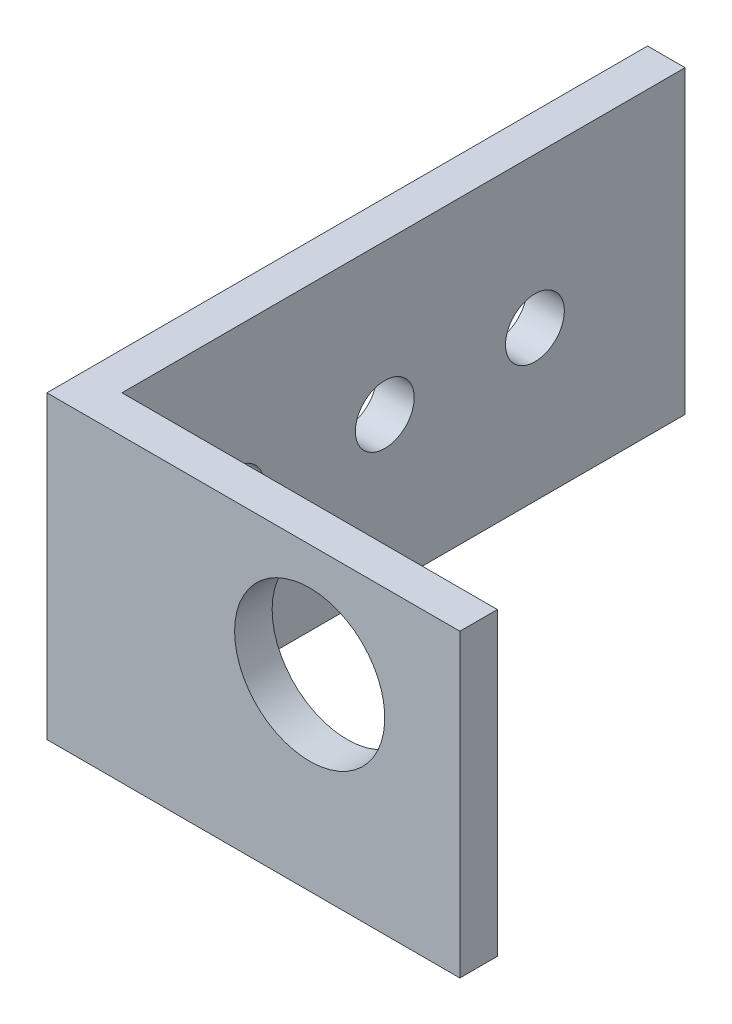
SolidWorks part; units mm, degrees
material "6061-T6 (SS)"
ref_plane "Front Plane" through (0, 0, 0) normal (0, 0, 1) x (1, 0, 0)
ref_plane "Top Plane" through (0, 0, 0) normal (0, 1, 0) x (1, 0, 0)
ref_plane "Right Plane" through (0, 0, 0) normal (1, 0, 0) x (0, 0, -1)
sketch "Sketch2" plane through (0, 0, 0) normal (0, 1, 0) x (1, 0, 0)
  line L0 (0, 0) -> (0, 50.8)
  line L1 (0, 50.8) -> (3.175, 50.8)
  line L2 (3.175, 50.8) -> (3.175, 3.175)
  line L3 (3.175, 3.175) -> (34.925, 3.175)
  line L4 (34.925, 3.175) -> (34.925, 0)
  line L5 (34.925, 0) -> (0, 0)
  dimension "D1" = 50.8
  dimension "D2" = 34.925
  dimension "D3" = 3.175
extrude "Boss-Extrude1" add sketch "Sketch2" along normal blind 25.4
sketch "Sketch3" plane through (0, 0, -3.175) normal (0, 0, -1) x (-1, 0, 0)
  line L0 (-34.925, 25.4) -> (-34.925, 0) construction
  line L2 (-34.925, 25.4) -> (-3.175, 25.4) construction
  circle A0 centre (-22.225, 15.875) radius 6.35
  dimension "D1" = 12.7
  dimension "D2" = 9.525
  dimension "D3" = 12.7
extrude "Cut-Extrude1" cut sketch "Sketch3" against normal through all
sketch "Sketch4" plane through (3.175, 0, 0) normal (1, 0, 0) x (0, 0, -1)
  line L1 (3.175, 25.4) -> (50.8, 25.4) construction
  line L2 (3.175, 0) -> (50.8, 0) construction
  line L3 (3.175, 25.4) -> (3.175, 0) construction
  circle A0 centre (25.4, 12.7) radius 2.4892
  circle A1 centre (12.7, 12.7) radius 2.4892
  circle A2 centre (38.1, 12.7) radius 2.4892
  dimension "D1" = 4.9784
  dimension "D2" = 9.525
  dimension "D3" = 12.7
  dimension "D4" = 12.7
  dimension "D5" = 12.7
  dimension "D6" = 12.7
extrude "Cut-Extrude2" cut sketch "Sketch4" against normal through all
